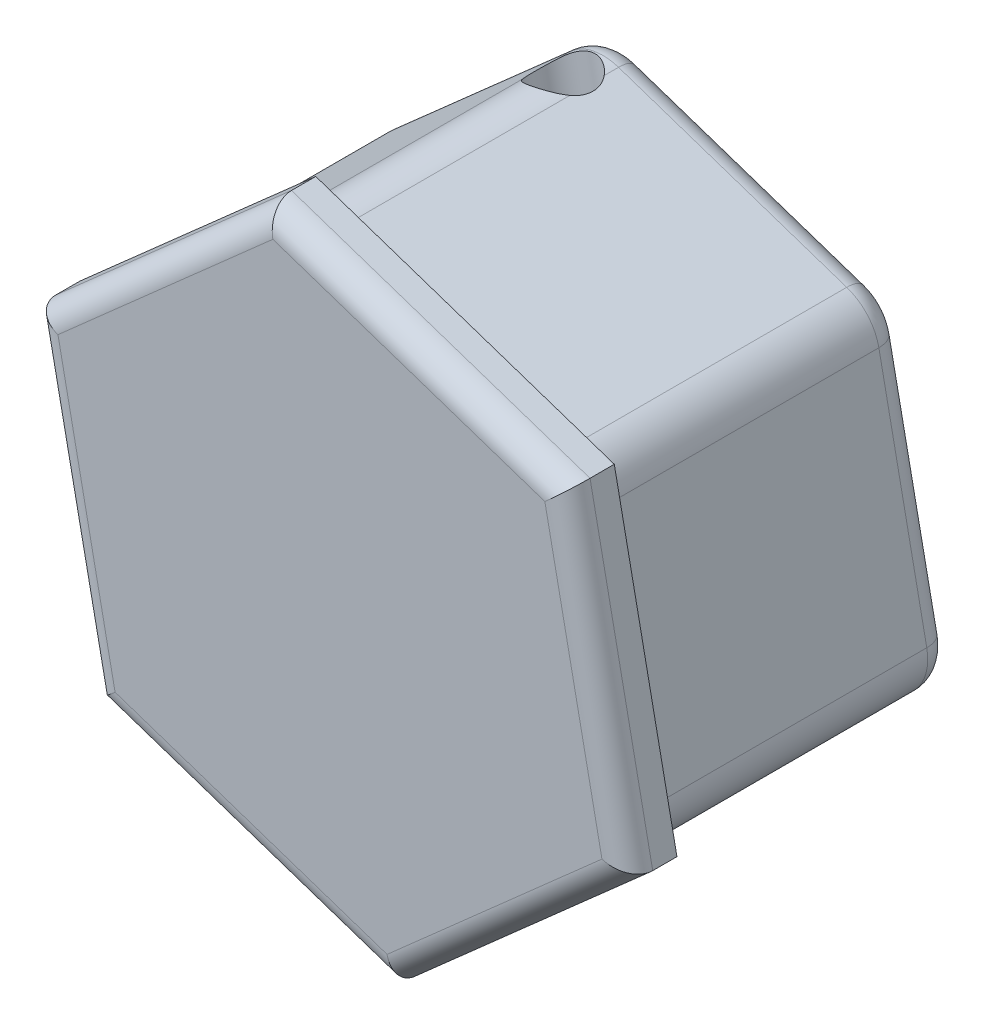
SolidWorks part; units mm, degrees
ref_plane "Płaszczyzna przednia" through (0, 0, 0) normal (0, 0, 1) x (1, 0, 0)
ref_plane "Płaszczyzna górna" through (0, 0, 0) normal (0, 1, 0) x (1, 0, 0)
ref_plane "Płaszczyzna prawa" through (0, 0, 0) normal (1, 0, 0) x (0, 0, -1)
sketch "Szkic1" plane through (0, 0, 0) normal (0, 0, 1) x (1, 0, 0)
  line L7 (1.7831, -4.5641) -> (-0.6537, 7.4307)
  line L8 (-0.6537, 7.4307) -> (-12.2599, 11.3178)
  line L9 (-12.2599, 11.3178) -> (-21.4293, 3.2101)
  line L10 (-21.4293, 3.2101) -> (-18.9925, -8.7847)
  line L11 (-18.9925, -8.7847) -> (-7.3863, -12.6718)
  line L12 (-7.3863, -12.6718) -> (1.7831, -4.5641)
  circle A0 centre (-9.8231, -0.677) radius 10.6 construction
  dimension "D1" = 21.2
extrude "Dodanie-wyciągnięcie1" add sketch "Szkic1" along normal blind 14.25
fillet "Zaokrąglenie1" radius 2 6 edges at (-0.6537, 7.4307, 7.125) (1.7831, -4.5641, 7.125) (-7.3863, -12.6718, 7.125) (-18.9925, -8.7847, 7.125) (-21.4293, 3.2101, 7.125) (-12.2599, 11.3178, 7.125)
sketch "Szkic3" plane through (0, 0, 14.25) normal (0, 0, 1) x (1, 0, 0)
  line L0 (-21.1995, 2.0785) -> (1.5532, -3.4325) construction
  line L1 (-13.125, 10.5529) -> (-6.5213, -11.9069) construction
  line L2 (1.5532, -3.4325) -> (-0.4238, 6.2991) construction
  line L3 (-0.0915, 7.9279) -> (-12.4094, 12.0533)
  line L4 (-12.4094, 12.0533) -> (-22.141, 3.4484)
  line L5 (-22.141, 3.4484) -> (-19.5548, -9.2819)
  line L6 (-19.5548, -9.2819) -> (-7.2369, -13.4074)
  line L7 (-7.2369, -13.4074) -> (2.4948, -4.8025)
  line L8 (2.4948, -4.8025) -> (-0.0915, 7.9279)
  circle A0 centre (-9.8231, -0.677) radius 11.25 construction
  dimension "D1" = 0
  dimension "D2" = 22.5
extrude "Dodanie-wyciągnięcie2" add sketch "Szkic3" against normal blind 2
fillet "Zaokrąglenie2" radius 1 12 edges at (-0.8855, 7.2258, 0) (0.5647, 1.4333, 0) (1.4897, -4.4658, 0) (-2.8016, -8.618, 0) (-7.4479, -12.3686, 0) (-13.1894, -10.7283, 0) (-18.7608, -8.5798, 0) (-20.2109, -2.7873, 0) (-21.136, 3.1118, 0) (-16.8446, 7.2639, 0) (-12.1983, 11.0146, 0) (-6.4568, 9.3743, 0)
ref_plane "Płaszczyzna1" through (-9.5659, -1.9433, 0) normal (0.98, 0.1991, 0) x (0, 0, -1)
ref_plane "Płaszczyzna2" through (-0.2573, 1.2663, 0) normal (-0.1991, 0.98, 0) x (0.98, 0.1991, 0)
fillet "Zaokrąglenie3" radius 1 6 edges at (-2.3711, -9.1049, 14.25) (-13.3959, -11.3446, 14.25) (-20.8479, -2.9168, 14.25) (-17.2752, 7.7509, 14.25) (-6.2504, 9.9906, 14.25) (1.2017, 1.5627, 14.25)
sketch "Szkic4" plane through (-0.2573, 1.2663, 0) normal (-0.1991, 0.98, 0) x (0.98, 0.1991, 0)
  line L0 (-9.7613, -10.9512) -> (-9.7613, 10.9512) construction
  line L2 (1.4887, -12.25) -> (-9.7613, -12.25) construction
  circle A0 centre (-9.7613, -2.3) radius 1.225
  point P4 (-9.7613, -13.9654)
  point P5 (-9.7613, -8.8382)
  dimension "D1" = 0
  dimension "D3" = 2.45
  dimension "D2" = 9.95
extrude "Wytnij-wyciągnięcie1" cut sketch "Szkic4" against normal through all both and the other way through all
